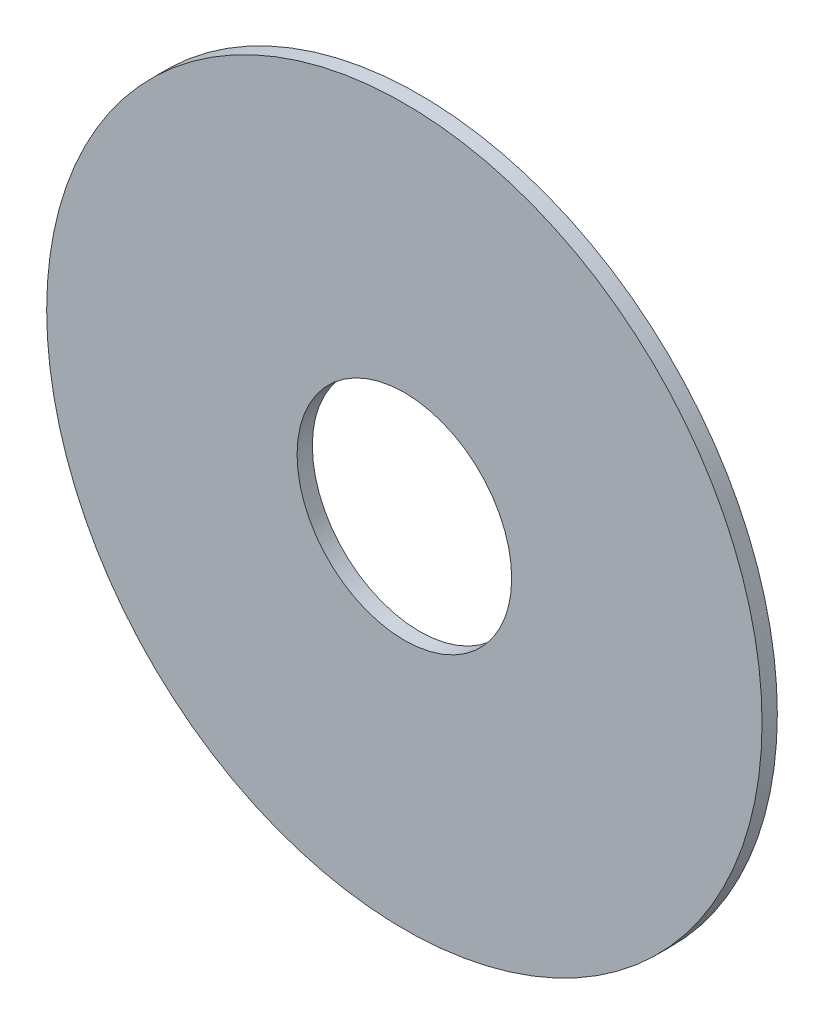
SolidWorks part; units mm, degrees
material "CA"
ref_plane "Front Plane" through (0, 0, 0) normal (0, 0, 1) x (1, 0, 0)
ref_plane "Top Plane" through (0, 0, 0) normal (0, 1, 0) x (1, 0, 0)
ref_plane "Right Plane" through (0, 0, 0) normal (1, 0, 0) x (0, 0, -1)
sketch "Sketch1" plane through (0, 0, 0) normal (0, 0, 1) x (1, 0, 0)
  circle A0 centre (0, 0) radius 19.05
  circle A1 centre (0, 0) radius 5.715
  dimension "D1" = 38.1
  dimension "D2" = 11.43
extrude "Boss-Extrude1" add sketch "Sketch1" along normal blind 0.8128
